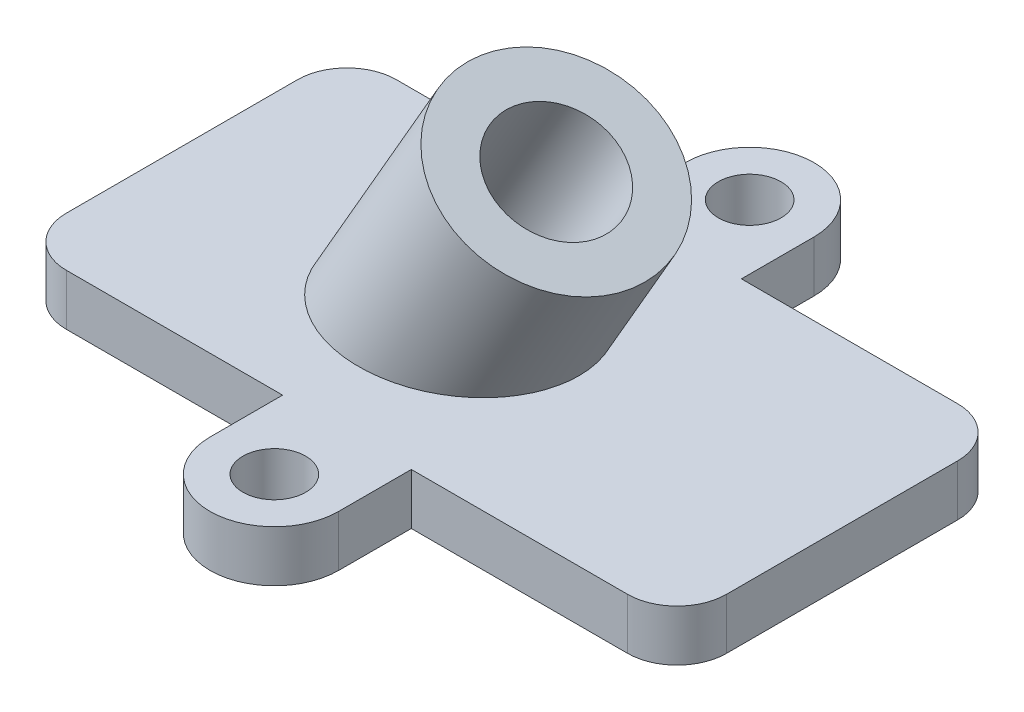
SolidWorks part; units mm, degrees
ref_plane "Front Plane" through (0, 0, 0) normal (0, 0, 1) x (1, 0, 0)
ref_plane "Top Plane" through (0, 0, 0) normal (0, 1, 0) x (1, 0, 0)
ref_plane "Right Plane" through (0, 0, 0) normal (1, 0, 0) x (0, 0, -1)
sketch "Sketch1" plane through (0, 0, 0) normal (0, 1, 0) x (1, 0, 0)
  line L0 (-100, 0) -> (100, 0) construction
  line L1 (-85, -50) -> (-19.5, -50)
  line L2 (-100, -35) -> (-100, 35)
  line L3 (-85, 50) -> (-19.5, 50)
  line L4 (100, -35) -> (100, 35)
  line L5 (-100, -50) -> (100, 50) construction
  line L6 (-100, 50) -> (100, -50) construction
  line L8 (-19.5, -50) -> (-19.5, -72)
  line L9 (19.5, -72) -> (19.5, -50)
  line L10 (19.5, -50) -> (85, -50)
  line L11 (19.5, 72) -> (19.5, 50)
  line L12 (-19.5, 50) -> (-19.5, 72)
  line L13 (19.5, 50) -> (85, 50)
  arc A0 (-19.5, -72) -> (19.5, -72) centre (0, -72) ccw
  circle A1 centre (0, -72) radius 9.5
  circle A2 centre (0, 72) radius 9.5
  arc A3 (-19.5, 72) -> (19.5, 72) centre (0, 72) cw
  arc A4 (-85, -50) -> (-100, -35) centre (-85, -35) cw
  arc A5 (85, -50) -> (100, -35) centre (85, -35) ccw
  arc A6 (85, 50) -> (100, 35) centre (85, 35) cw
  arc A7 (-100, 35) -> (-85, 50) centre (-85, 35) cw
  point P0 (0, 0)
  point P14 (0, 0)
  point P35 (0, 0)
  point P36 (0, 0)
  dimension "D4" = 19.5
  dimension "D5" = 19
  dimension "D6" = 15
  dimension "D1" = 200
  dimension "D2" = 100
  dimension "D3" = 22
extrude "Boss-Extrude1" add sketch "Sketch1" against normal blind 15.5
ref_plane "Plane1" through (25, 43.3013, 0) normal (0.5, 0.866, 0) x (0, 0, -1)
sketch "Sketch2" plane through (25, 43.3013, 0) normal (0.5, 0.866, 0) x (0, 0, -1)
  line L0 (-35, -86.6025) -> (35, -86.6025) construction
  circle A0 centre (0, 13.3975) radius 31
  point P2 (0, 0)
  dimension "D1" = 62
  dimension "D2" = 100
extrude "Boss-Extrude2" add sketch "Sketch2" against normal up to surface (75.6329 mm away)
sketch "Sketch3" plane through (25, 43.3013, 0) normal (0.5, 0.866, 0) x (0.866, -0.5, 0)
  circle A0 centre (-13.3975, 0) radius 17.5
  circle A1 centre (-13.3975, 0) radius 31 construction
  dimension "D1" = 35
extrude "Cut-Extrude1" cut sketch "Sketch3" against normal up to next
